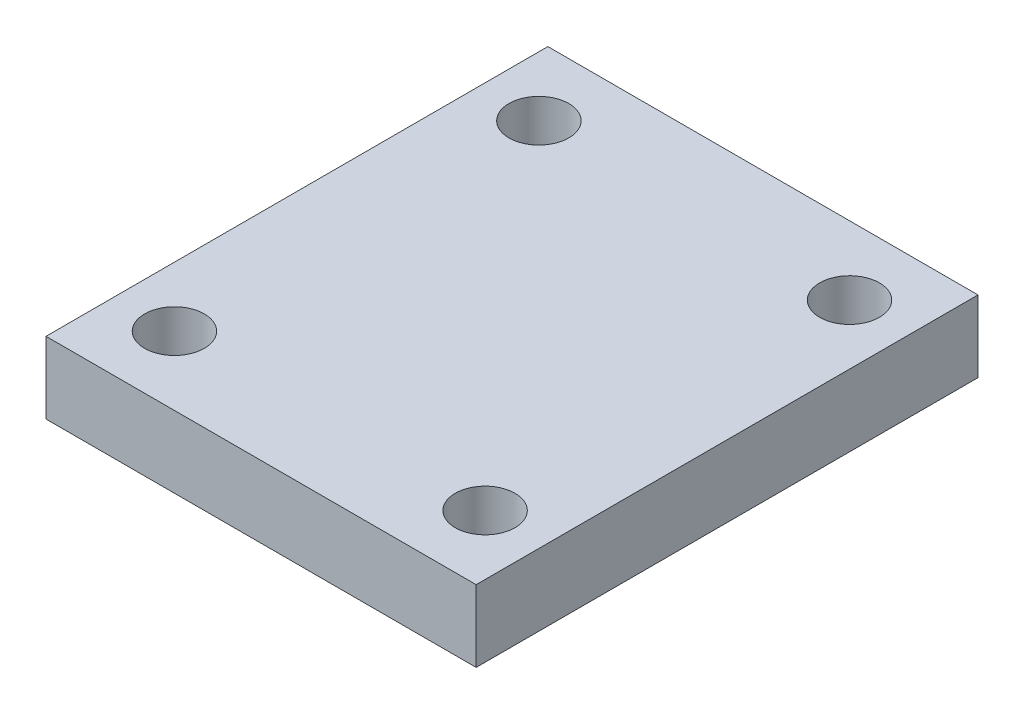
SolidWorks part; units mm, degrees
ref_plane "Front Plane" through (0, 0, 0) normal (0, 0, 1) x (1, 0, 0)
ref_plane "Top Plane" through (0, 0, 0) normal (0, 1, 0) x (1, 0, 0)
ref_plane "Right Plane" through (0, 0, 0) normal (1, 0, 0) x (0, 0, -1)
sketch "Sketch1" plane through (0, 0, 0) normal (0, 1, 0) x (1, 0, 0)
  line L1 (-18, -21) -> (18, -21)
  line L2 (-18, -21) -> (-18, 21)
  line L3 (-18, 21) -> (18, 21)
  line L4 (18, -21) -> (18, 21)
  line L5 (-18, -21) -> (18, 21) construction
  line L6 (-18, 21) -> (18, -21) construction
  line L7 (-55, 0) -> (55, 0) construction
  line L8 (0, -55) -> (0, 55) construction
  circle A0 centre (-13, 15.25) radius 2.5
  circle A1 centre (-13, -15.25) radius 2.5
  circle A2 centre (13, -15.25) radius 2.5
  circle A3 centre (13, 15.25) radius 2.5
  point P0 (0, 0)
  dimension "D3" = 5
  dimension "D1" = 36
  dimension "D2" = 42
  dimension "D4" = 5.75
  dimension "D5" = 5
extrude "Boss-Extrude1" add sketch "Sketch1" along normal blind 6
